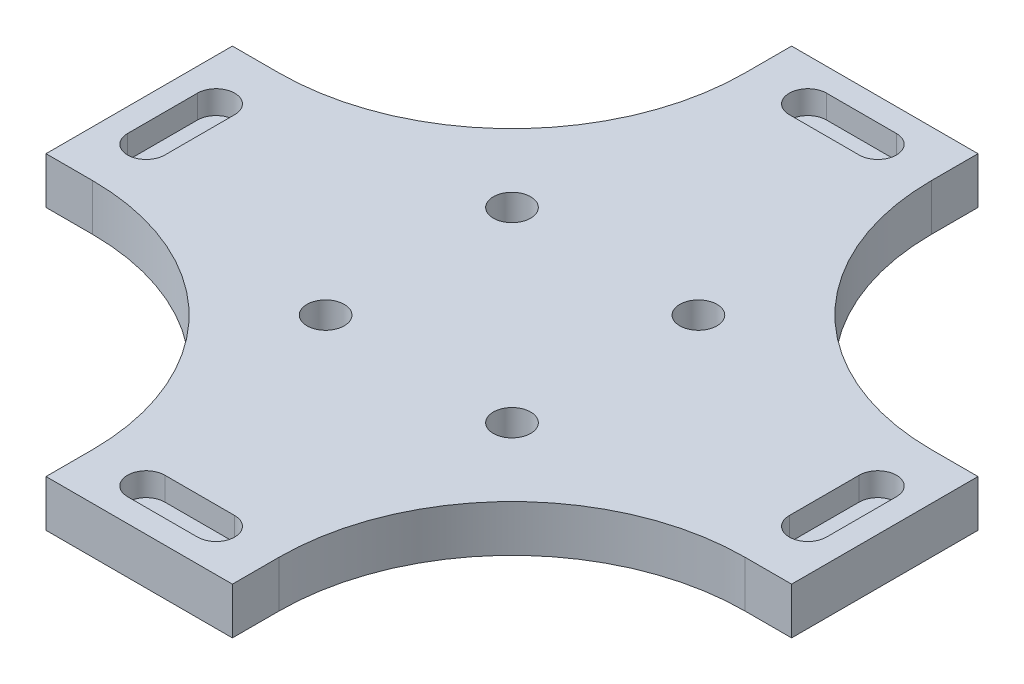
SolidWorks part; units mm, degrees
ref_plane "Front Plane" through (0, 0, 0) normal (0, 0, 1) x (1, 0, 0)
ref_plane "Top Plane" through (0, 0, 0) normal (0, 1, 0) x (1, 0, 0)
ref_plane "Right Plane" through (0, 0, 0) normal (1, 0, 0) x (0, 0, -1)
sketch "Sketch1" plane through (0, 0, 0) normal (0, 1, 0) x (1, 0, 0)
  line L0 (-7.1729, 15.8251) -> (-7.1729, 20.8251)
  line L1 (-7.1729, 20.8251) -> (12.8271, 20.8251)
  line L2 (12.8271, 20.8251) -> (12.8271, 15.8251)
  line L3 (2.8271, 20.8251) -> (2.8271, -19.1749) construction
  line L4 (-32.1729, -29.1749) -> (-37.1729, -29.1749)
  line L5 (-37.1729, -29.1749) -> (-37.1729, -9.1749)
  line L6 (-37.1729, -9.1749) -> (-32.1729, -9.1749)
  line L7 (12.8271, -54.1749) -> (12.8271, -59.1749)
  line L8 (12.8271, -59.1749) -> (-7.1729, -59.1749)
  line L9 (-7.1729, -59.1749) -> (-7.1729, -54.1749)
  line L10 (37.8271, -9.1749) -> (42.8271, -9.1749)
  line L11 (42.8271, -9.1749) -> (42.8271, -29.1749)
  line L12 (42.8271, -29.1749) -> (37.8271, -29.1749)
  line L13 (-32.1729, -9.1749) -> (-7.1729, -9.1749) construction
  line L14 (-7.1729, -9.1749) -> (-7.1729, 15.8251) construction
  line L15 (-0.9229, 16.3251) -> (6.5771, 16.3251) construction
  line L16 (-0.9229, 18.3251) -> (6.5771, 18.3251)
  line L17 (-0.9229, 14.3251) -> (6.5771, 14.3251)
  line L18 (36.3271, -15.4249) -> (36.3271, -22.9249)
  line L19 (40.3271, -15.4249) -> (40.3271, -22.9249)
  line L20 (38.3271, -15.4249) -> (38.3271, -22.9249) construction
  line L21 (6.5771, -52.6749) -> (-0.9229, -52.6749)
  line L22 (6.5771, -56.6749) -> (-0.9229, -56.6749)
  line L23 (6.5771, -54.6749) -> (-0.9229, -54.6749) construction
  line L24 (-30.6729, -22.9249) -> (-30.6729, -15.4249)
  line L25 (-34.6729, -22.9249) -> (-34.6729, -15.4249)
  line L26 (-32.6729, -22.9249) -> (-32.6729, -15.4249) construction
  circle A0 centre (2.8271, -19.1749) radius 12.8777 construction
  arc A1 (-7.1729, 15.8251) -> (-32.1729, -9.1749) centre (-32.1729, 15.8251) cw
  arc A2 (-32.1729, -29.1749) -> (-7.1729, -54.1749) centre (-32.1729, -54.1749) cw
  arc A3 (12.8271, -54.1749) -> (37.8271, -29.1749) centre (37.8271, -54.1749) cw
  arc A4 (12.8271, 15.8251) -> (37.8271, -9.1749) centre (37.8271, 15.8251) ccw
  circle A5 centre (-7.1729, -9.1749) radius 2
  circle A6 centre (12.8271, -9.1749) radius 2
  circle A7 centre (12.8271, -29.1749) radius 2
  circle A8 centre (-7.1729, -29.1749) radius 2
  arc A9 (-0.9229, 18.3251) -> (-0.9229, 14.3251) centre (-0.9229, 16.3251) ccw
  arc A10 (6.5771, 14.3251) -> (6.5771, 18.3251) centre (6.5771, 16.3251) ccw
  arc A11 (40.3271, -15.4249) -> (36.3271, -15.4249) centre (38.3271, -15.4249) ccw
  arc A12 (36.3271, -22.9249) -> (40.3271, -22.9249) centre (38.3271, -22.9249) ccw
  arc A13 (6.5771, -56.6749) -> (6.5771, -52.6749) centre (6.5771, -54.6749) ccw
  arc A14 (-0.9229, -52.6749) -> (-0.9229, -56.6749) centre (-0.9229, -54.6749) ccw
  arc A15 (-34.6729, -22.9249) -> (-30.6729, -22.9249) centre (-32.6729, -22.9249) ccw
  arc A16 (-30.6729, -15.4249) -> (-34.6729, -15.4249) centre (-32.6729, -15.4249) ccw
  point P22 (2.8271, -19.1749)
  point P28 (2.8271, 16.3251)
  point P35 (2.8271, -19.1749)
  point P45 (38.3271, -19.1749)
  point P52 (2.8271, -54.6749)
  point P59 (-32.6729, -19.1749)
  point P64 (2.8271, -19.1749)
  dimension "D5" = 4
  dimension "D6" = 4
  dimension "D9" = 2
  dimension "D1" = 20
  dimension "D2" = 5
  dimension "D3" = 5
  dimension "D4" = 40
  dimension "D8" = 7.5
  dimension "D10" = 2.5
  dimension "D7" = 4
  dimension "D11" = 4
extrude "Boss-Extrude1" add sketch "Sketch1" along normal blind 5 contours A1 L6 L5 L4 A2 L9 L8 L7 A3 L12 L11 L10 A4 L2 L1 L0
sketch "Sketch2" plane through (0, 0, 0) normal (0, -1, 0) x (1, 0, 0)
  line L0 (40.7571, 25.8723) -> (36.0275, 25.8723)
  line L5 (-3.8703, 57.1049) -> (9.5246, 57.1049)
  line L6 (-3.8703, 57.1049) -> (-3.8703, 52.3752)
  line L7 (-3.8703, 52.3752) -> (9.5246, 52.3752)
  line L8 (9.5246, 57.1049) -> (9.5246, 52.3752)
  line L9 (-3.8703, 57.1049) -> (9.5246, 52.3752) construction
  line L10 (-3.8703, 52.3752) -> (9.5246, 57.1049) construction
  line L11 (40.7571, 25.8723) -> (40.7571, 12.4775)
  line L12 (40.7571, 12.4775) -> (36.0275, 12.4775)
  line L13 (36.0275, 25.8723) -> (36.0275, 12.4775)
  line L14 (9.5246, -18.7551) -> (9.5246, -14.0254)
  line L15 (9.5246, -18.7551) -> (-3.8703, -18.7551)
  line L16 (-3.8703, -18.7551) -> (-3.8703, -14.0254)
  line L17 (9.5246, -14.0254) -> (-3.8703, -14.0254)
  line L18 (-35.1028, 12.4775) -> (-30.3732, 12.4775)
  line L19 (-35.1028, 12.4775) -> (-35.1028, 25.8723)
  line L20 (-35.1028, 25.8723) -> (-30.3732, 25.8723)
  line L21 (-30.3732, 12.4775) -> (-30.3732, 25.8723)
  circle A0 centre (2.8271, 19.1749) radius 6.6974 construction
  point P0 (2.8271, 54.7401)
  point P22 (2.8271, 19.1749)
  dimension "D1" = 4
extrude "Boss-Extrude2" add sketch "Sketch2" against normal blind 2.5 contours L0 L13 L12 L11
